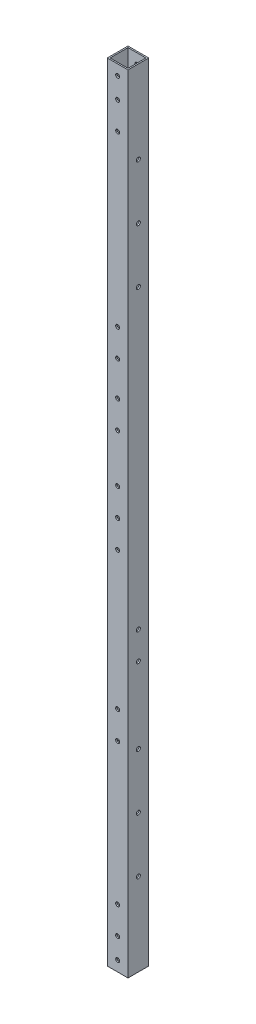
SolidWorks part; units mm, degrees
material "Thornel Mat VMA"
ref_plane "前视基准面" through (0, 0, 0) normal (0, 0, 1) x (1, 0, 0)
ref_plane "上视基准面" through (0, 0, 0) normal (0, 1, 0) x (1, 0, 0)
ref_plane "右视基准面" through (0, 0, 0) normal (1, 0, 0) x (0, 0, -1)
sketch "草图1" plane through (0, 0, 0) normal (0, 1, 0) x (1, 0, 0)
  line L1 (-7.5, -7.5) -> (7.5, -7.5)
  line L2 (-7.5, -7.5) -> (-7.5, 7.5)
  line L3 (-7.5, 7.5) -> (7.5, 7.5)
  line L4 (7.5, -7.5) -> (7.5, 7.5)
  line L5 (-7.5, -7.5) -> (7.5, 7.5) construction
  line L6 (-7.5, 7.5) -> (7.5, -7.5) construction
  point P0 (0, 0)
  dimension "D1" = 15
  dimension "D2" = 15
extrude "拉伸-薄壁1" add sketch "草图1" along normal blind 570 thin thin type one direction reverse wall 1
sketch "草图2" plane through (0, 0, 0) normal (0, 0, 1) x (1, 0, 0)
  line L0 (0, 0) -> (0, 570) construction
  line L1 (-7.5, 570) -> (7.5, 570) construction
  line L2 (-1000, 285) -> (49000, 285) construction
  line L3 (-7.5, 0) -> (7.5, 0) construction
  circle A0 centre (0, 7.5) radius 1.45
  circle A1 centre (0, 22.5) radius 1.45
  circle A2 centre (0, 42.5) radius 1.45
  circle A3 centre (0, 527.5) radius 1.45
  circle A4 centre (0, 547.5) radius 1.45
  circle A5 centre (0, 562.5) radius 1.45
  circle A6 centre (0, 285) radius 1.45
  circle A7 centre (0, 305) radius 1.45
  circle A8 centre (0, 265) radius 1.45
  circle A9 centre (0, 405) radius 1.45
  circle A10 centre (0, 385) radius 1.45
  circle A11 centre (0, 165) radius 1.45
  circle A12 centre (0, 145) radius 1.45
  circle A13 centre (0, 340) radius 1.45
  circle A14 centre (0, 360) radius 1.45
  point P14 (0, 285)
  dimension "D1" = 2.9
  dimension "D5" = 2.9
  dimension "D8" = 20
  dimension "D9" = 100
  dimension "D12" = 35
  dimension "D13" = 20
  dimension "D2" = 7.5
  dimension "D3" = 15
  dimension "D4" = 20
  dimension "D6" = 20
  dimension "D7" = 20
  dimension "D10" = 20
  dimension "D11" = 120
extrude "切除-拉伸1" cut sketch "草图2" against normal through all and the other way blind 10
sketch "草图3" plane through (7.5, 0, 0) normal (1, 0, 0) x (0, 0, -1)
  line L0 (0, 0) -> (0, 570) construction
  line L1 (-7.5, 570) -> (7.5, 570) construction
  line L2 (-7.5, 0) -> (7.5, 0) construction
  line L3 (-1000, 285) -> (49000, 285) construction
  circle A0 centre (0, 60) radius 1.45
  circle A1 centre (0, 100) radius 1.45
  circle A2 centre (0, 470) radius 1.45
  circle A3 centre (0, 510) radius 1.45
  circle A4 centre (0, 140) radius 1.45
  circle A5 centre (0, 430) radius 1.45
  circle A6 centre (0, 195) radius 1.45
  circle A7 centre (0, 215) radius 1.45
  point P14 (0, 285)
  dimension "D1" = 2.9
  dimension "D5" = 20
  dimension "D6" = 70
  dimension "D2" = 60
  dimension "D3" = 40
  dimension "D4" = 40
extrude "切除-拉伸2" cut sketch "草图3" against normal through all
